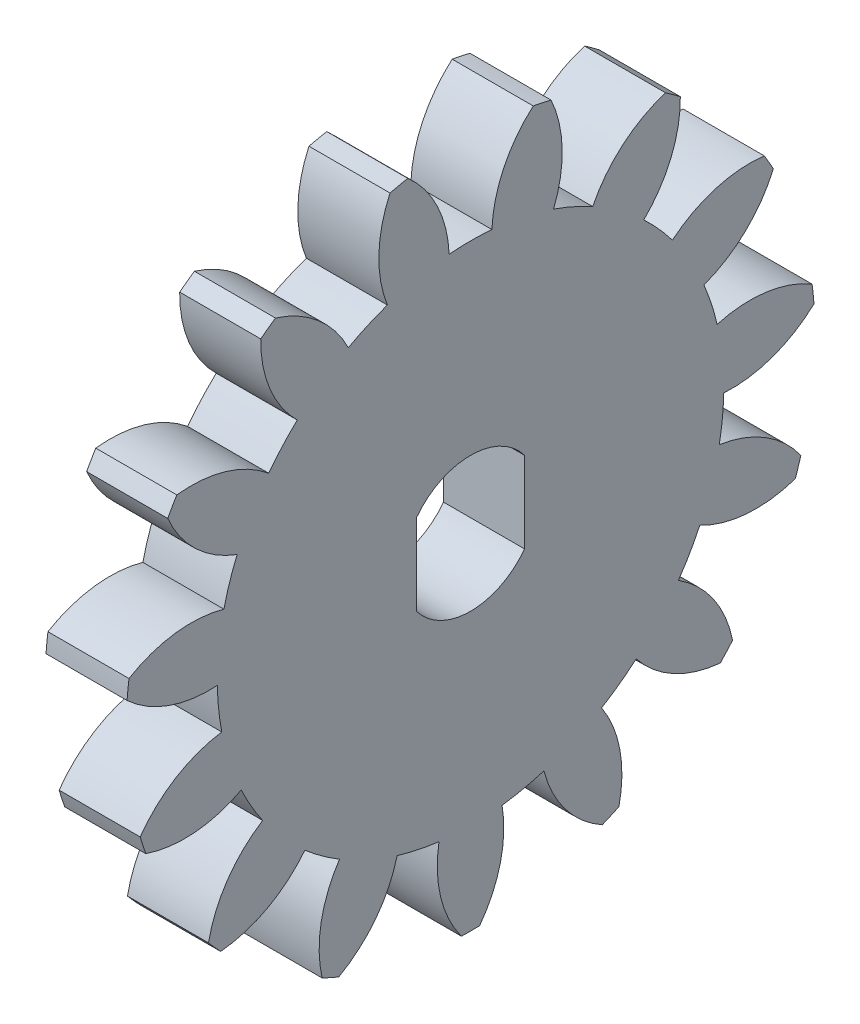
SolidWorks part; units mm, degrees
ref_plane "Plane1" through (0, 0, 0) normal (0, 0, 1) x (1, 0, 0)
ref_plane "Plane2" through (0, 0, 0) normal (0, 1, 0) x (1, 0, 0)
ref_plane "Plane3" through (0, 0, 0) normal (1, 0, 0) x (0, 0, -1)
sketch "HoldingSke" plane through (0, 0, 0) normal (0, 1, 0) x (1, 0, 0)
  line L0 (0, 0) -> (0.644, -0.1725)
  line L1 (-15, 0) -> (100, 0) construction
  line L2 (0, 0) -> (-2.1039, 2.3779)
  line L3 (0, 0) -> (-11.863, 4.5341)
  line L4 (0, 0) -> (8.3417, 2.2352)
  line L5 (0, 0) -> (-46.8476, -17.4728)
  line L6 (0, 0) -> (-2.4869, -1.6779)
  line L7 (-2.1039, 2.3779) -> (8.6586, 51.2059)
  line L8 (-76.2, 54.61) -> (-75.3, 54.61)
  line L9 (-71.009, 38.7566) -> (-53.1078, 45.2721)
  line L10 (-76.2, 71.12) -> (104.1128, 71.12)
  line L11 (0, 0) -> (-3, 0)
  line L12 (-76.2, 101.6) -> (-76.147, 101.6)
  line L13 (24.9733, 27.94) -> (52.9518, 28.4284)
  line L14 (24.9733, 27.94) -> (24.9743, 27.94)
  line L15 (24.9733, 27.94) -> (100.4006, 29.5858)
  line L16 (-63.627, -1.5) -> (-12.827, -1.5)
  circle A0 centre (0, 0) radius 2.5
  circle A1 centre (0, 0) radius 9.374
  circle A2 centre (0, 0) radius 37.5
  circle A3 centre (0, 0) radius 2.5
  dimension "MHD" = 18.748
  dimension "Hub_dia" = 75
  dimension "Bore" = 5
  dimension "MBD" = 5
  dimension "Num_teeth" = 15
  dimension "Pitch" = 0.6667
  dimension "Overall_len" = 50
  dimension "Show_teeth" = 15
  dimension "Thickness" = 3
  dimension "OAL" = 50.0001
  dimension "T_dim" = 0.9
  dimension "Ap" = 20
  dimension "H" = 19.05
  dimension "Pitch_radius" = 180.3128
  dimension "Width" = 3
  dimension "Backlash" = 0.053
  dimension "Addendum_fac" = 1
  dimension "Dedendum_fac" = 1.25
  dimension "Clearance_fac" = 0.25
  dimension "Dedendum_add" = 0.001
  dimension "Module" = 1.5
sketch "BasProSke" plane through (0, 0, 0) normal (0, 1, 0) x (1, 0, 0)
  line L0 (-10, 0) -> (60, 0) construction
  line L1 (0, 0) -> (0, 12.75)
  line L2 (0, 0) -> (3, 0)
  line L3 (3, 0) -> (3, 12.75)
  line L4 (3, 12.75) -> (0, 12.75)
  dimension "Thickness" = 3
  dimension "Diameter" = 25.5
revolve "Base-Revolve" add sketch "BasProSke" angle 360 about L0
sketch "TooCutSke" plane through (0, 0, 0) normal (1, 0, 0) x (0, 0, -1)
  line L1 (0, 0) -> (0, 107) construction
  line L2 (0, 0) -> (-1.2686, 11.1782) construction
  line L3 (0, 0) -> (-4.6563, 21.9061) construction
  line L4 (-1.2686, 11.1782) -> (-2.3281, 10.953) construction
  arc A0 (0.7915, 9.3405) -> (-0.7915, 9.3405) centre (0, 0) ccw
  arc A1 (2.3447, 12.5584) -> (-2.3447, 12.5584) centre (0, 0) ccw
  circle A2 centre (0, 0) radius 11.25 construction
  circle A3 centre (0, 0) radius 10.5715 construction
  arc A4 (-0.7915, 9.3405) -> (-2.3447, 12.5584) centre (-5.2877, 9.1541) ccw
  arc A5 (2.3447, 12.5584) -> (0.7915, 9.3405) centre (5.2877, 9.1541) ccw
  dimension "Root_dia" = 18.748
  dimension "Overcut_dia" = 25.5508
  dimension "Pitch_dia" = 22.5
  dimension "Base_dia" = 21.1431
  dimension "Flank_rad" = 4.5
  dimension "Half_ang" = 12
  dimension "Half_CT" = 1.0832
extrude "ToothCut" cut sketch "TooCutSke" along normal through all
fillet "Breaks" [suppressed] radius 0.03
fillet "RootFillets" [suppressed] radius 0.376
pattern_circular "TeethCuts" count 15 every 24 about axis through (-10, 0, 0) along (1, 0, 0) of "ToothCut", "RootFillets", "Breaks"
sketch "HubNeaOneSke" plane through (0, 0, 0) normal (-1, 0, 0) x (0, 0, 1)
  circle A0 centre (0, 0) radius 9.374
  dimension "Diameter" = 18.748
extrude "HubNearOne" [suppressed] add sketch "HubNeaOneSke" along normal blind 47.0001
sketch "HubNeaBotSke" plane through (0, 0, 0) normal (-1, 0, 0) x (0, 0, 1)
  circle A0 centre (0, 0) radius 9.374
  dimension "Diameter" = 18.748
extrude "HubNearBoth" [suppressed] add sketch "HubNeaBotSke" along normal blind 23.5
ref_plane "FarPln" through (3, 0, 0) normal (1, 0, 0) x (0, 0, -1)
sketch "HubFarSke" plane through (3, 0, 0) normal (1, 0, 0) x (0, 0, -1)
  circle A0 centre (0, 0) radius 9.374
  dimension "Diameter" = 18.748
extrude "HubFar" [suppressed] add sketch "HubFarSke" along normal blind 23.5
sketch "BorSke" plane through (0, 0, 0) normal (1, 0, 0) x (0, 0, -1)
  circle A0 centre (0, 0) radius 2.5
  dimension "Diameter" = 5
extrude "Bore" cut sketch "BorSke" along normal mid plane 100.0001
sketch "KeySke" plane through (0, 0, 0) normal (1, 0, 0) x (0, 0, -1)
  line L0 (-1, 0) -> (-1, 3.4)
  line L1 (-1, 3.4) -> (1, 3.4)
  line L2 (1, 3.4) -> (1, 0)
  line L3 (0, 0) -> (0, 34) construction
  line L4 (-1, 0) -> (1, 0)
  dimension "Offset" = 3.4
  dimension "Width" = 2
extrude "Keyway" [suppressed] cut sketch "KeySke" along normal mid plane 100.0001
pattern_circular "Keyway2" [suppressed] count 2 every 90 about axis through (-10, 0, 0) along (1, 0, 0)
sketch "Esquisse1" plane through (3, 0, 0) normal (1, 0, 0) x (0, 0, -1)
  line L0 (0, 0) -> (23.4065, 0) construction
  line L1 (0, 0) -> (0, 11.3692) construction
  line L2 (0, 2.5) -> (0, -2.5) construction
  line L3 (-2, 2.5) -> (2, 2.5) construction
  line L4 (-2, 1.5) -> (-2, -1.5)
  line L5 (-2, -2.5) -> (2, -2.5) construction
  line L6 (2, 1.5) -> (2, -1.5)
  circle A0 centre (0, 0) radius 2.5 construction
  arc A1 (-2, 1.5) -> (-2, -1.5) centre (0, 0) ccw
  arc A2 (2, -1.5) -> (2, 1.5) centre (0, 0) ccw
  dimension "D1" = 4
  dimension "D2" = 5
  dimension "D4" = 3
  dimension "D5" = 3
extrude "Boss.-Extru.1" add sketch "Esquisse1" against normal blind 3
equation "' \"Module@HoldingSke\" = 6.35"
equation "' \"Num_teeth@HoldingSke\" = 12"
equation "' \"Ap@HoldingSke\" =  20"
equation "' \"Ap@HoldingSke\" = 20"
equation "' \"Width@HoldingSke\" = 0.5 * 25.4"
equation "' \"Hub_dia@HoldingSke\"= 1 * 25.4"
equation "' \"Hub_dia@HoldingSke\" = 1 * 25.4"
equation "' \"Overall_len@HoldingSke\" = 1.0 * 25.4"
equation "' \"Bore@HoldingSke\" = 0.75 * 25.4"
equation "' \"T_dim@HoldingSke\" = 0.1 * 25.4"
equation "' \"Width@KeySke\" = 0.25 * 25.4"
equation "' \"Show_teeth@HoldingSke\" = 13"
equation "' \"Backlash@HoldingSke\" = 0.009 * 25.4"
equation "' \"Addendum_fac@HoldingSke\" = 1.0"
equation "' \"Dedendum_fac@HoldingSke\" = 1.25"
equation "' \"Dedendum_add@HoldingSke\" = 0.00005 * 25.4"
equation "' \"Clearance_fac@HoldingSke\" = 0.25"
equation "\"Pitch@HoldingSke\" = 1 / \"Module@HoldingSke\""
equation "\"Overcut_dia@TooCutSke\" = (\"Num_teeth@HoldingSke\" + 2 * \"Addendum_fac@HoldingSke\") / \"Pitch@HoldingSke\" + 0.002 * 25.4"
equation "\"Pitch_dia@TooCutSke\" = \"Num_teeth@HoldingSke\" / \"Pitch@HoldingSke\""
equation "\"Base_dia@TooCutSke\" = \"Num_teeth@HoldingSke\" / \"Pitch@HoldingSke\" * cos((\"Ap@HoldingSke\"  * 3.14159265 / 180))"
equation "\"Root_dia@TooCutSke\" = (\"Num_teeth@HoldingSke\" + 2) / \"Pitch@HoldingSke\" - 2 * (\"Addendum_fac@HoldingSke\" + \"Dedendum_fac@HoldingSke\") / \"Pitch@HoldingSke\" - \"Dedendum_add@HoldingSke\" * 2"
equation "\"Half_ang@TooCutSke\" = 180 / \"Num_teeth@HoldingSke\""
equation "\"Half_CT@TooCutSke\" = \"Num_teeth@HoldingSke\" / \"Pitch@HoldingSke\" * sin((3.14159265 / 2 / \"Num_teeth@HoldingSke\")) / 2 - 7 * \"Backlash@HoldingSke\" / 4"
equation "\"Flank_rad@TooCutSke\" = \"Num_teeth@HoldingSke\" / \"Pitch@HoldingSke\" / 5"
equation "\"Radius@RootFillets\" = \"Clearance_fac@HoldingSke\" / \"Pitch@HoldingSke\" + \"Dedendum_add@HoldingSke\""
equation "\"Break_rad@Breaks\" = 0.02 / \"Pitch@HoldingSke\""
equation "\"Thickness@HoldingSke\" = \"Width@HoldingSke\""
equation "\"OAL@HoldingSke\" = \"Thickness@HoldingSke\""
equation "\"MHD@HoldingSke\" = (\"Num_teeth@HoldingSke\" + 2) / \"Pitch@HoldingSke\" - 2 * (\"Addendum_fac@HoldingSke\" + \"Dedendum_fac@HoldingSke\")  / \"Pitch@HoldingSke\" - \"Dedendum_add@HoldingSke\" * 2"
equation "\"MBD@HoldingSke\" = (\"Num_teeth@HoldingSke\" + 2) / \"Pitch@HoldingSke\" - 2 * (\"Addendum_fac@HoldingSke\" + \"Dedendum_fac@HoldingSke\")  / \"Pitch@HoldingSke\" - \"Dedendum_add@HoldingSke\" * 2 - 0.002 * 25.4"
equation "\"MHD@HoldingSke\" = ((sgn( \"MHD@HoldingSke\" - \"Hub_dia@HoldingSke\" )-1)*( \"MHD@HoldingSke\" - \"Hub_dia@HoldingSke\" ))/-2+ \"Hub_dia@HoldingSke\""
equation "\"MBD@HoldingSke\" = ((sgn( \"MBD@HoldingSke\" - \"Bore@HoldingSke\" )-1)*( \"MBD@HoldingSke\" - \"Bore@HoldingSke\" ))/-2+ \"Bore@HoldingSke\""
equation "\"OAL@HoldingSke\" = ((sgn( \"OAL@HoldingSke\" - \"Overall_len@HoldingSke\" )+1)*( \"OAL@HoldingSke\" - \"Overall_len@HoldingSke\" ))/2 + \"Overall_len@HoldingSke\" + 0.000002 * 25.4"
equation "\"Num_teeth@TeethCuts\" = int( \"Show_teeth@HoldingSke\" ) + 1"
equation "\"Num_teeth@TeethCuts\" = ((sgn( \"Num_teeth@TeethCuts\" - \"Num_teeth@HoldingSke\" )-1)*( \"Num_teeth@TeethCuts\" - \"Num_teeth@HoldingSke\" ))/-2+ \"Num_teeth@HoldingSke\""
equation "\"Num_teeth@TeethCuts\" = ((sgn( \"Num_teeth@TeethCuts\" - 2.0)+1)*( \"Num_teeth@TeethCuts\" - 2.0))/2 +2.0"
equation "\"Angle@TeethCuts\" = 360.0 / \"Num_teeth@HoldingSke\""
equation "\"Diameter@BasProSke\" = (\"Num_teeth@HoldingSke\" + 2 * \"Addendum_fac@HoldingSke\") / \"Pitch@HoldingSke\""
equation "\"Thickness@BasProSke\"  = \"Thickness@HoldingSke\""
equation "' \"Fillet_rad@BasProSke\" =  \"Thickness@HoldingSke\" * 0.05"
equation "' \"Fillet_rad@BasProSke\" = \"Thickness@HoldingSke\" * 0.05"
equation "\"MHD@HoldingSke\" = ((sgn( \"MHD@HoldingSke\" - \"Root_dia@TooCutSke\" )-1)*( \"MHD@HoldingSke\" - \"Root_dia@TooCutSke\" ))/-2+ \"Root_dia@TooCutSke\""
equation "\"Diameter@HubNeaOneSke\" = \"MHD@HoldingSke\""
equation "\"Length@HubNearOne\" = \"OAL@HoldingSke\" - \"Thickness@BasProSke\""
equation "\"Diameter@HubNeaBotSke\" = \"MHD@HoldingSke\""
equation "\"Length@HubNearBoth\" = ( \"OAL@HoldingSke\" - \"Thickness@BasProSke\" ) / 2.0"
equation "\"Thickness@FarPln\" = \"Thickness@BasProSke\""
equation "\"Diameter@HubFarSke\" = \"MHD@HoldingSke\""
equation "\"Length@HubFar\" = ( \"OAL@HoldingSke\" - \"Thickness@BasProSke\" ) / 2.0"
equation "\"Diameter@BorSke\" = \"MBD@HoldingSke\""
equation "\"D1@Bore\" = \"OAL@HoldingSke\" * 2.0"
equation "\"D1@Keyway\" = \"OAL@HoldingSke\" * 2.0"
equation "\"Offset@KeySke\" = \"T_dim@HoldingSke\" + \"MBD@HoldingSke\" / 2.0"
